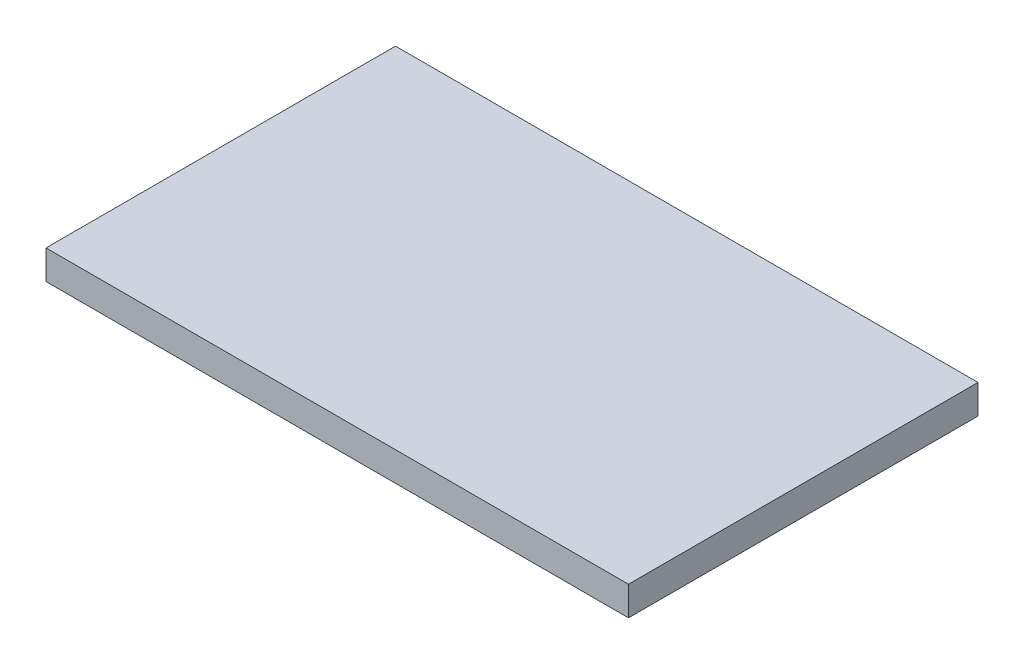
SolidWorks part; units mm, degrees
ref_plane "Front Plane" through (0, 0, 0) normal (0, 0, 1) x (1, 0, 0)
ref_plane "Top Plane" through (0, 0, 0) normal (0, 1, 0) x (1, 0, 0)
ref_plane "Right Plane" through (0, 0, 0) normal (1, 0, 0) x (0, 0, -1)
sketch "Sketch1" plane through (0, 0, 0) normal (0, 1, 0) x (1, 0, 0)
  line L1 (0, 0) -> (100, 0)
  line L2 (0, 0) -> (0, 60)
  line L3 (0, 60) -> (100, 60)
  line L4 (100, 0) -> (100, 60)
  dimension "D1" = 60
  dimension "D2" = 100
extrude "Boss-Extrude1" add sketch "Sketch1" along normal blind 5
